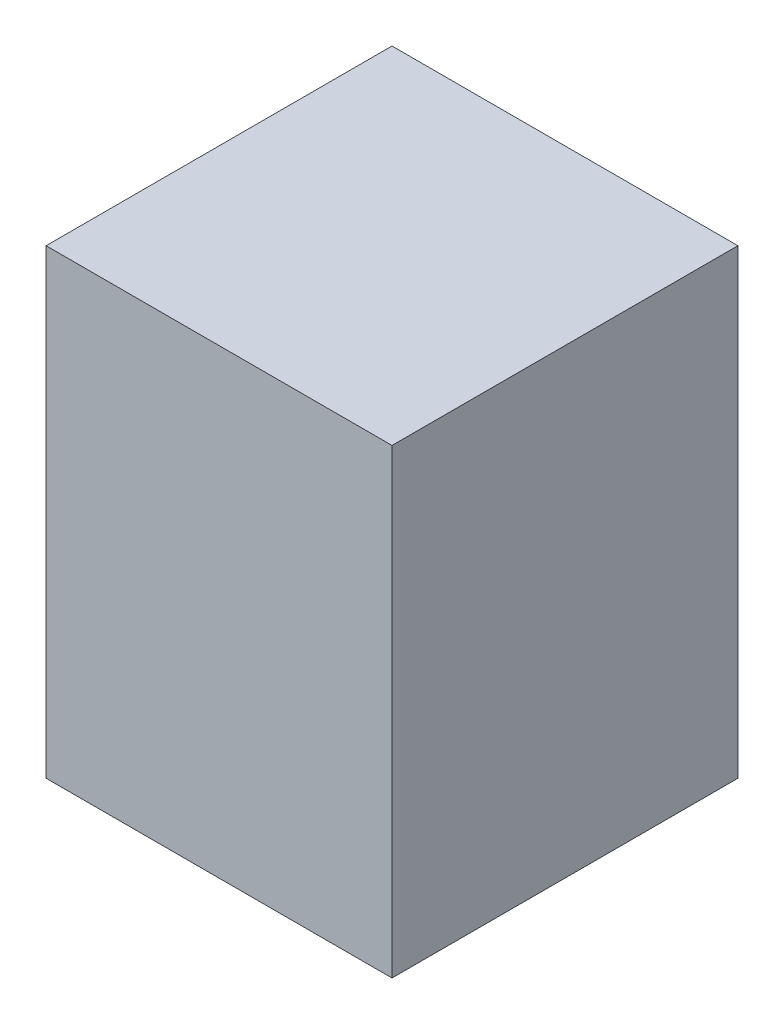
SolidWorks part; units mm, degrees
ref_plane "Front Plane" through (0, 0, 0) normal (0, 0, 1) x (1, 0, 0)
ref_plane "Top Plane" through (0, 0, 0) normal (0, 1, 0) x (1, 0, 0)
ref_plane "Right Plane" through (0, 0, 0) normal (1, 0, 0) x (0, 0, -1)
sketch "Sketch2" plane through (0, 0, 0) normal (0, 1, 0) x (1, 0, 0)
  line L1 (-15, -15) -> (15, -15)
  line L2 (-15, -15) -> (-15, 15)
  line L3 (-15, 15) -> (15, 15)
  line L4 (15, -15) -> (15, 15)
  line L5 (-15, -15) -> (15, 15) construction
  line L6 (-15, 15) -> (15, -15) construction
  point P0 (0, 0)
  dimension "D1" = 30
  dimension "D2" = 30
extrude "Boss-Extrude1" add sketch "Sketch2" along normal blind 40
sketch "Sketch3" plane through (0, 0, 0) normal (0, -1, 0) x (1, 0, 0)
  line L0 (0, 10.5) -> (0, -10.5) construction
  line L1 (-10.5, 0) -> (10.5, 0) construction
  circle A0 centre (0, 10.5) radius 1.5
  circle A1 centre (10.5, 0) radius 1.5
  circle A2 centre (0, -10.5) radius 1.5
  circle A3 centre (-10.5, 0) radius 1.5
  point P8 (0, 0)
  point P9 (0, 0)
  dimension "D1" = 3
  dimension "D2" = 21
  dimension "D3" = 21
extrude "Cut-Extrude1" cut sketch "Sketch3" against normal blind 17
